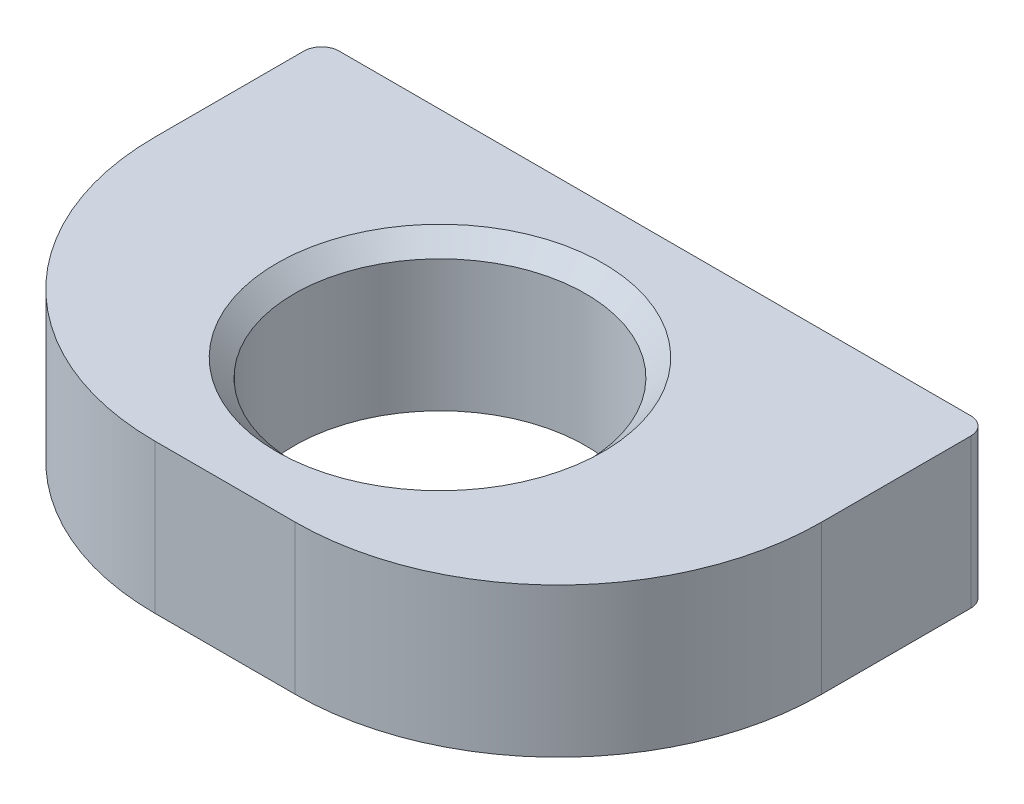
SolidWorks part; units mm, degrees
ref_plane "Front Plane" through (0, 0, 0) normal (0, 0, 1) x (1, 0, 0)
ref_plane "Top Plane" through (0, 0, 0) normal (0, 1, 0) x (1, 0, 0)
ref_plane "Right Plane" through (0, 0, 0) normal (1, 0, 0) x (0, 0, -1)
sketch "Sketch1" plane through (0, 0, 0) normal (0, 1, 0) x (1, 0, 0)
  line L1 (-19, 12.25) -> (19, 12.25)
  line L2 (-19, 12.25) -> (-19, -12.25)
  line L3 (-19, -12.25) -> (19, -12.25)
  line L4 (19, 12.25) -> (19, -12.25)
  circle A0 centre (0, 0) radius 8.3
  dimension "D5" = 16.6
  dimension "D1" = 38
  dimension "D2" = 24.5
  dimension "D3" = 12.25
  dimension "D4" = 19
extrude "Boss-Extrude1" add sketch "Sketch1" along normal blind 8.5
fillet "Fillet1" radius 15 2 edges at (19, 4.25, 12.25) (-19, 4.25, 12.25)
fillet "Fillet2" radius 1 2 edges at (-19, 4.25, -12.25) (19, 4.25, -12.25)
chamfer "Chamfer1" distance 1 angle 45 1 edges at (0, 8.5, 8.3)
